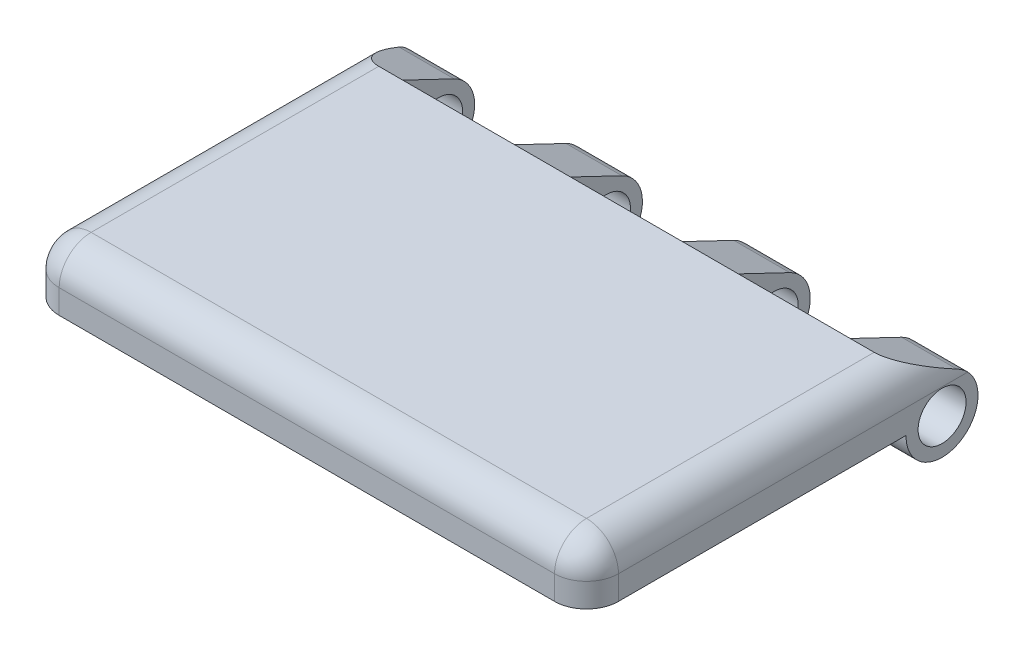
SolidWorks part; units mm, degrees
ref_plane "Front Plane" through (0, 0, 0) normal (0, 0, 1) x (1, 0, 0)
ref_plane "Top Plane" through (0, 0, 0) normal (0, 1, 0) x (1, 0, 0)
ref_plane "Right Plane" through (0, 0, 0) normal (1, 0, 0) x (0, 0, -1)
sketch "Sketch1" plane through (0, 0, 0) normal (0, 1, 0) x (1, 0, 0)
  line L1 (17.5, 10) -> (-17.5, 10)
  line L2 (17.5, 10) -> (17.5, -10)
  line L3 (17.5, -10) -> (-17.5, -10)
  line L4 (-17.5, 10) -> (-17.5, -10)
  line L5 (17.5, 10) -> (-17.5, -10) construction
  line L6 (17.5, -10) -> (-17.5, 10) construction
  point P0 (0, 0)
  dimension "D1" = 35
  dimension "D2" = 20
extrude "Boss-Extrude1" add sketch "Sketch1" along normal blind 3.5
sketch "Sketch3" plane through (17.5, 0, 0) normal (1, 0, 0) x (0, 0, -1)
  line L0 (10, 3.5) -> (13.2203, 1.9585)
  circle A0 centre (12.2489, -0.071) radius 1.5
  arc A2 (13.2203, 1.9585) -> (10, 0) centre (12.2489, -0.071) cw
  line M5 (10, 0) -> (10, 3.5)
  dimension "D1" = 3
extrude "Boss-Extrude2" add sketch "Sketch3" against normal blind 3.5 contours A2 L0 A0 M5
pattern_linear "LPattern1" count 4 spacing 10.5 along (-1, 0, 0) of "Boss-Extrude2"
fillet "Fillet1" radius 2 5 edges at (17.5, 3.5, 0) (0, 3.5, 10) (-17.5, 3.5, 0) (-17.5, 1.75, 10) (17.5, 1.75, 10)
